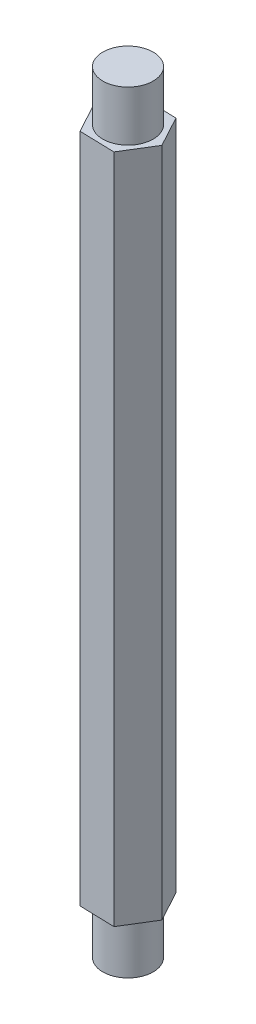
SolidWorks part; units mm, degrees
ref_plane "Front Plane" through (0, 0, 0) normal (0, 0, 1) x (1, 0, 0)
ref_plane "Top Plane" through (0, 0, 0) normal (0, 1, 0) x (1, 0, 0)
ref_plane "Right Plane" through (0, 0, 0) normal (1, 0, 0) x (0, 0, -1)
sketch "Sketch1" plane through (0, 0, 0) normal (0, 1, 0) x (1, 0, 0)
  circle A0 centre (0, 0) radius 1.5
  dimension "D1" = 3
extrude "Boss-Extrude1" add sketch "Sketch1" along normal blind 3
sketch "Sketch2" plane through (0, 3, 0) normal (0, 1, 0) x (1, 0, 0)
  line L0 (0, 0) -> (-1.5, 0) construction
  line L1 (-0.9892, 1.828) -> (-2.0777, 0.0574)
  line L2 (-2.0777, 0.0574) -> (-1.0885, -1.7706)
  line L3 (-1.0885, -1.7706) -> (0.9892, -1.828)
  line L4 (0.9892, -1.828) -> (2.0777, -0.0574)
  line L5 (2.0777, -0.0574) -> (1.0885, 1.7706)
  line L6 (1.0885, 1.7706) -> (-0.9892, 1.828)
  circle A0 centre (0, 0) radius 1.8 construction
  circle A1 centre (0, 0) radius 1.5 construction
  dimension "D2" = 178.418
  dimension "D1" = 1.8
extrude "Boss-Extrude2" add sketch "Sketch2" along normal blind 40
sketch "Sketch3" plane through (0, 43, 0) normal (0, 1, 0) x (1, 0, 0)
  circle A0 centre (0, 0) radius 1.5
  dimension "D1" = 3
extrude "Boss-Extrude3" add sketch "Sketch3" along normal blind 3
